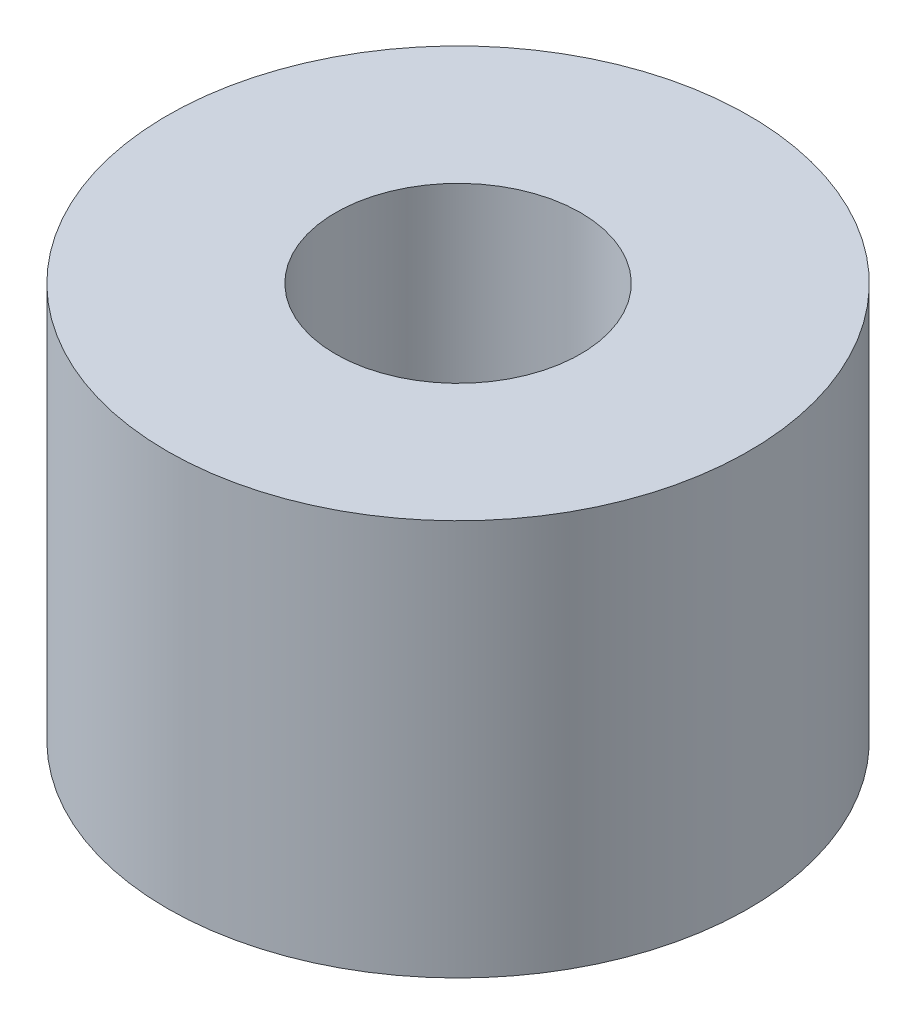
SolidWorks part; units mm, degrees
ref_plane "Front Plane" through (0, 0, 0) normal (0, 0, 1) x (1, 0, 0)
ref_plane "Top Plane" through (0, 0, 0) normal (0, 1, 0) x (1, 0, 0)
ref_plane "Right Plane" through (0, 0, 0) normal (1, 0, 0) x (0, 0, -1)
sketch "Sketch1" plane through (0, 0, 0) normal (0, 0, 1) x (1, 0, 0)
  line L0 (2.475, 8) -> (2.475, 0)
  line L1 (55, 0) -> (-55, 0) construction
  line L2 (2.475, 0) -> (5.875, 0)
  line L3 (5.875, 0) -> (5.875, 8)
  line L4 (5.875, 8) -> (2.475, 8)
  line L5 (0, -55) -> (0, 55) construction
  line L6 (0, 21.7486) -> (0, -11.951) construction
  dimension "D1" = 8
  dimension "D2" = 3.4
  dimension "D3" = 5.875
revolve "Revolve1" add sketch "Sketch1" angle 360 about L6
